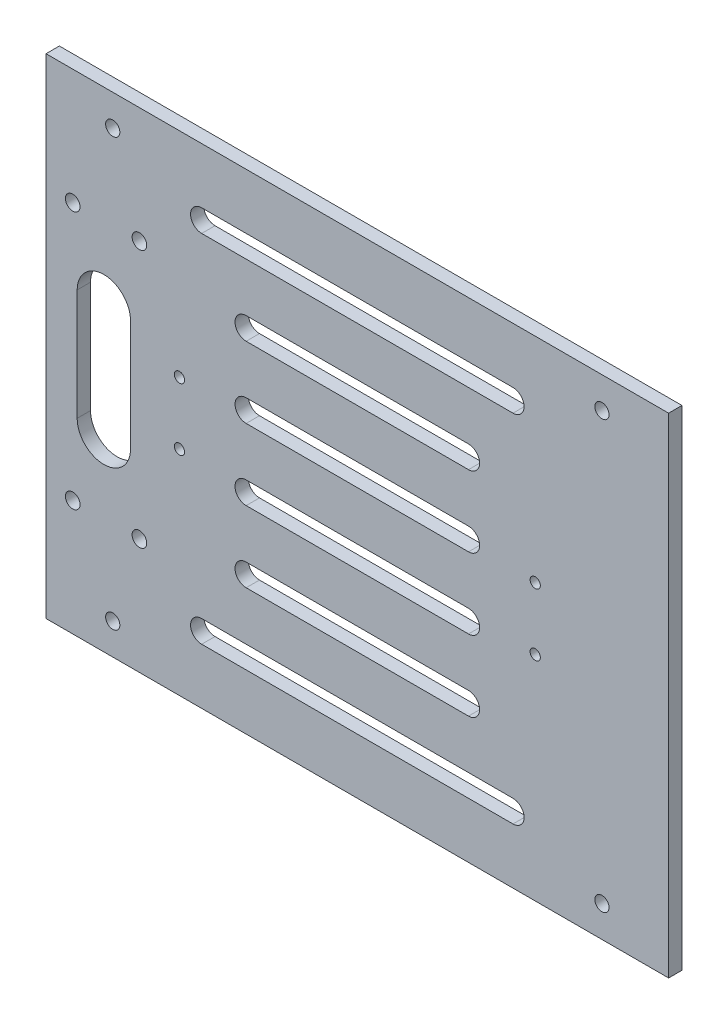
SolidWorks part; units mm, degrees
material "Thornel Mat VMA"
ref_plane "前视基准面" through (0, 0, 0) normal (0, 0, 1) x (1, 0, 0)
ref_plane "上视基准面" through (0, 0, 0) normal (0, 1, 0) x (1, 0, 0)
ref_plane "右视基准面" through (0, 0, 0) normal (1, 0, 0) x (0, 0, -1)
sketch "草图1" plane through (0, 0, 0) normal (0, 0, 1) x (1, 0, 0)
  line L1 (-70, -55) -> (70, -55)
  line L2 (-70, -55) -> (-70, 55)
  line L3 (-70, 55) -> (70, 55)
  line L4 (70, -55) -> (70, 55)
  line L5 (-70, -55) -> (70, 55) construction
  line L6 (-70, 55) -> (70, -55) construction
  point P0 (0, 0)
  dimension "D1" = 140
  dimension "D2" = 110
extrude "凸台-拉伸1" add sketch "草图1" along normal blind 3
sketch "草图2" plane through (0, 0, 0) normal (0, 0, -1) x (-1, 0, 0)
  line L0 (49, 29) -> (64, 29) construction
  line L1 (64, 29) -> (64, -29) construction
  line L2 (64, -29) -> (49, -29) construction
  line L3 (49, -29) -> (49, 29) construction
  line L4 (70, 55) -> (70, -55) construction
  circle A0 centre (64, 29) radius 1.65
  circle A1 centre (64, -29) radius 1.65
  circle A2 centre (49, 29) radius 1.65
  circle A3 centre (49, -29) radius 1.65
  point P8 (64, 0)
  point P11 (70, 0)
  dimension "D4" = 3.3
  dimension "D1" = 15
  dimension "D2" = 58
  dimension "D3" = 6
extrude "切除-拉伸1" cut sketch "草图2" against normal through all
sketch "草图3" plane through (0, 0, 0) normal (0, 0, -1) x (-1, 0, 0)
  line L0 (-40, 7) -> (40, 7) construction
  line L1 (40, 7) -> (40, -7) construction
  line L2 (40, -7) -> (-40, -7) construction
  line L3 (-40, -7) -> (-40, 7) construction
  circle A0 centre (-40, 7) radius 1.15
  circle A1 centre (-40, -7) radius 1.15
  circle A2 centre (40, 7) radius 1.15
  circle A3 centre (40, -7) radius 1.15
  point P8 (40, 0)
  point P9 (0, 7)
  dimension "D1" = 2.3
  dimension "D2" = 80
  dimension "D3" = 14
extrude "切除-拉伸2" cut sketch "草图3" against normal through all
sketch "草图4" plane through (0, 0, 3) normal (0, 0, 1) x (1, 0, 0)
  line L0 (-25, 40) -> (25, 40) construction
  line L1 (-25, 42.5) -> (25, 42.5)
  line L2 (-25, 37.5) -> (25, 37.5)
  line L3 (-25, 24) -> (25, 24) construction
  line L4 (-25, 26.5) -> (25, 26.5)
  line L5 (-25, 21.5) -> (25, 21.5)
  line L6 (-25, 8) -> (25, 8) construction
  line L7 (-25, 10.5) -> (25, 10.5)
  line L8 (-25, 5.5) -> (25, 5.5)
  line L9 (-25, -8) -> (25, -8) construction
  line L10 (-25, -5.5) -> (25, -5.5)
  line L11 (-25, -10.5) -> (25, -10.5)
  line L12 (-25, -24) -> (25, -24) construction
  line L13 (-25, -21.5) -> (25, -21.5)
  line L14 (-25, -26.5) -> (25, -26.5)
  line L15 (-25, -40) -> (25, -40) construction
  line L16 (-25, -37.5) -> (25, -37.5)
  line L17 (-25, -42.5) -> (25, -42.5)
  arc A0 (-25, 42.5) -> (-25, 37.5) centre (-25, 40) ccw
  arc A1 (25, 37.5) -> (25, 42.5) centre (25, 40) ccw
  arc A2 (-25, 26.5) -> (-25, 21.5) centre (-25, 24) ccw
  arc A3 (25, 21.5) -> (25, 26.5) centre (25, 24) ccw
  arc A4 (-25, 10.5) -> (-25, 5.5) centre (-25, 8) ccw
  arc A5 (25, 5.5) -> (25, 10.5) centre (25, 8) ccw
  arc A6 (-25, -5.5) -> (-25, -10.5) centre (-25, -8) ccw
  arc A7 (25, -10.5) -> (25, -5.5) centre (25, -8) ccw
  arc A8 (-25, -21.5) -> (-25, -26.5) centre (-25, -24) ccw
  arc A9 (25, -26.5) -> (25, -21.5) centre (25, -24) ccw
  arc A10 (-25, -37.5) -> (-25, -42.5) centre (-25, -40) ccw
  arc A11 (25, -42.5) -> (25, -37.5) centre (25, -40) ccw
  point P2 (0, 40)
  point P12 (0, 24)
  point P19 (0, 8)
  point P26 (0, -8)
  point P33 (0, -24)
  point P40 (0, -40)
  dimension "D1" = 40
  dimension "D2" = 50
  dimension "D3" = 5
  dimension "D4" = 6
extrude "切除-拉伸3" cut sketch "草图4" against normal blind 10
sketch "草图5" plane through (0, 0, 3) normal (0, 0, 1) x (1, 0, 0)
  line L0 (-35, 40) -> (35, 40) construction
  line L1 (-35, 42.5) -> (35, 42.5)
  line L2 (-35, 37.5) -> (35, 37.5)
  line L3 (-25, 37.5) -> (25, 37.5) construction
  arc A0 (-35, 42.5) -> (-35, 37.5) centre (-35, 40) ccw
  arc A1 (35, 37.5) -> (35, 42.5) centre (35, 40) ccw
  point P3 (0, 40)
  point P10 (33.3429, 40)
  point P11 (-25, 40)
  point P12 (-38.5996, 40)
  point P13 (0, 0)
  point P14 (0, 42.5)
  point P15 (-39.0502, 40)
  point P16 (0, 0)
  dimension "D1" = 70
extrude "切除-拉伸4" cut sketch "草图5" against normal blind 10
mirror "镜向1" about plane through (0, 0, 0) normal (0, 1, 0) of "切除-拉伸4"
sketch "草图7" plane through (0, 0, 3) normal (0, 0, 1) x (1, 0, 0)
  line L0 (-57, -12.5) -> (-57, 12.5) construction
  line L1 (-63, -12.5) -> (-63, 12.5)
  line L2 (-51, -12.5) -> (-51, 12.5)
  line L3 (-70, 55) -> (-70, -55) construction
  arc A0 (-63, -12.5) -> (-51, -12.5) centre (-57, -12.5) ccw
  arc A1 (-51, 12.5) -> (-63, 12.5) centre (-57, 12.5) ccw
  point P2 (-57, 0)
  point P7 (0, 0)
  point P10 (-70, 0)
  point P11 (-60.869, 0)
  dimension "D2" = 6
  dimension "D1" = 25
  dimension "D3" = 13
extrude "切除-拉伸5" cut sketch "草图7" against normal blind 10
sketch "草图8" plane through (0, 0, 3) normal (0, 0, 1) x (1, 0, 0)
  line L0 (-55, -48) -> (-55, 48) construction
  line L1 (-55, 48) -> (55, 48) construction
  line L2 (55, 48) -> (55, -48) construction
  line L3 (55, -48) -> (-55, -48) construction
  line L4 (-70, 55) -> (-70, -55) construction
  line L5 (-70, -55) -> (70, -55) construction
  circle A0 centre (55, -48) radius 1.6
  circle A1 centre (-55, -48) radius 1.6
  circle A2 centre (-55, 48) radius 1.6
  circle A3 centre (55, 48) radius 1.6
  point P10 (-70, 0)
  point P11 (-55, 0)
  point P12 (0, -48)
  point P15 (0, -55)
  point P16 (55, 0)
  point P17 (0, 48)
  dimension "D1" = 3.2
  dimension "D2" = 110
  dimension "D3" = 96
extrude "切除-拉伸6" cut sketch "草图8" against normal blind 10
